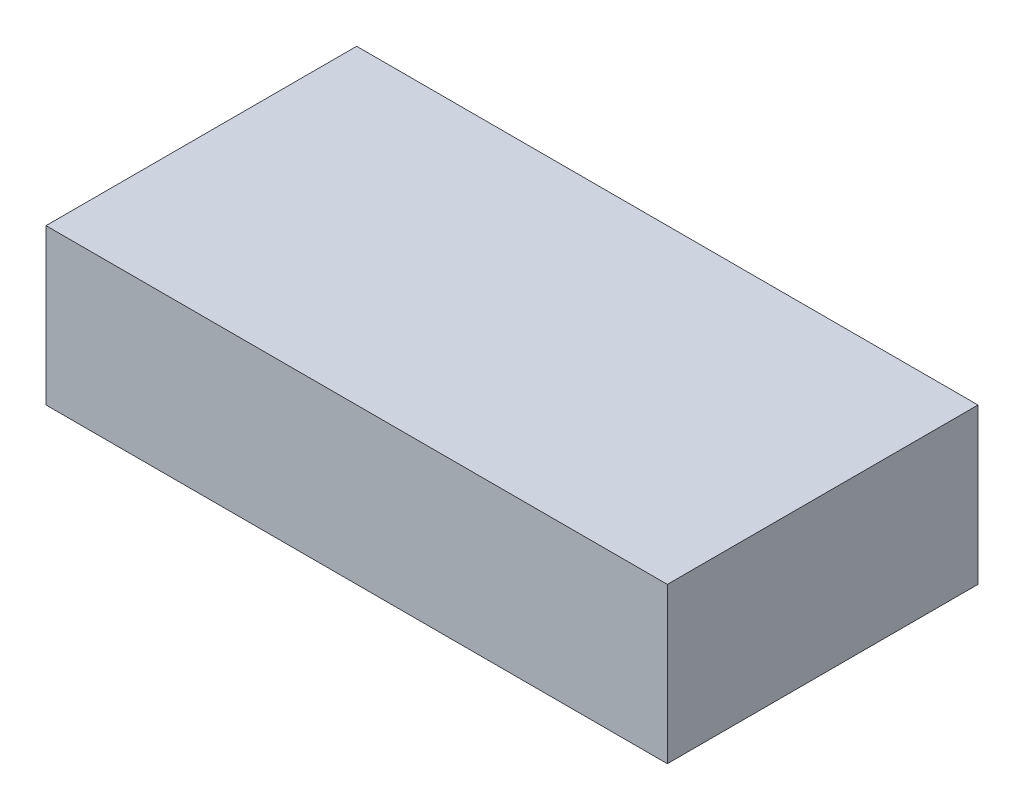
SolidWorks part; units mm, degrees
ref_plane "Front Plane" through (0, 0, 0) normal (0, 0, 1) x (1, 0, 0)
ref_plane "Top Plane" through (0, 0, 0) normal (0, 1, 0) x (1, 0, 0)
ref_plane "Right Plane" through (0, 0, 0) normal (1, 0, 0) x (0, 0, -1)
sketch "Sketch1" plane through (0, 0, 0) normal (0, 1, 0) x (1, 0, 0)
  line L0 (0, 0) -> (40, 0)
  line L1 (40, 0) -> (40, 20)
  line L2 (40, 20) -> (0, 20)
  line L3 (0, 20) -> (0, 0)
extrude "Boss-Extrude1" add sketch "Sketch1" along normal blind 10
